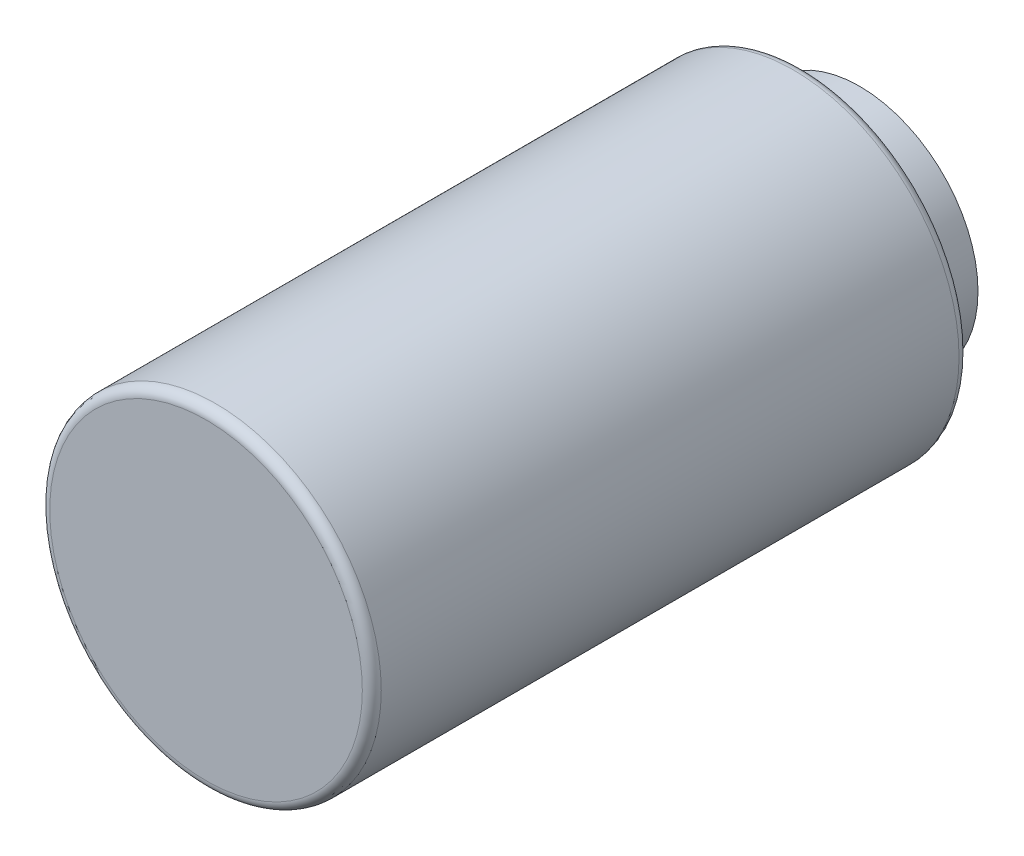
SolidWorks part; units mm, degrees
ref_plane "Front Plane" through (0, 0, 0) normal (0, 0, 1) x (1, 0, 0)
ref_plane "Top Plane" through (0, 0, 0) normal (0, 1, 0) x (1, 0, 0)
ref_plane "Right Plane" through (0, 0, 0) normal (1, 0, 0) x (0, 0, -1)
sketch "Sketch1" plane through (0, 0, 0) normal (0, 0, 1) x (1, 0, 0)
  circle A0 centre (0, 0) radius 17.5
  dimension "D1" = 35
extrude "Boss-Extrude1" add sketch "Sketch1" along normal blind 63
sketch "Sketch2" plane through (0, 0, 0) normal (0, 0, -1) x (-1, 0, 0)
  circle A0 centre (0, 0) radius 12.5
  dimension "D1" = 25
extrude "Boss-Extrude2" add sketch "Sketch2" along normal blind 6
fillet "Fillet1" radius 1 2 edges at (17.5, 0, 63) (17.5, 0, 0)
